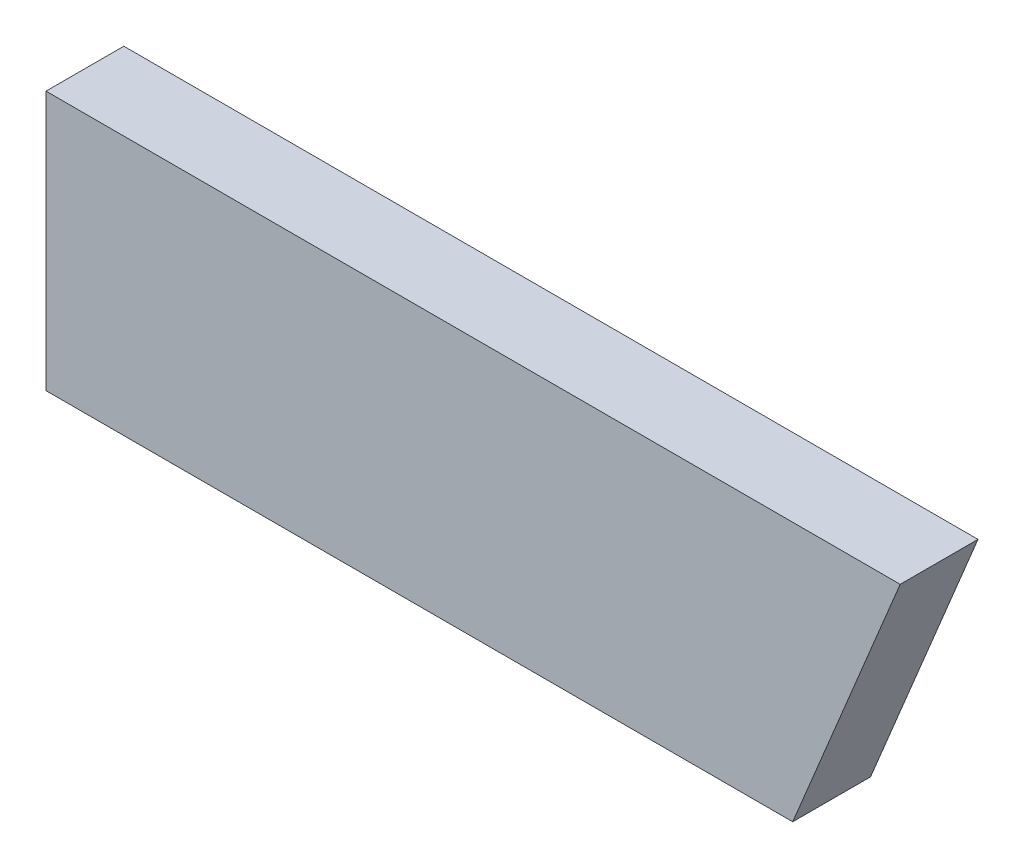
SolidWorks part; units mm, degrees
material "Pine"
ref_plane "Front Plane" through (0, 0, 0) normal (0, 0, 1) x (1, 0, 0)
ref_plane "Top Plane" through (0, 0, 0) normal (0, 1, 0) x (1, 0, 0)
ref_plane "Right Plane" through (0, 0, 0) normal (1, 0, 0) x (0, 0, -1)
sketch "Sketch2" plane through (0, 0, 0) normal (0, 0, 1) x (1, 0, 0)
  line L0 (-528.0858, 1843.9468) -> (-737.1845, 1843.9468)
  line L1 (-737.1845, 1780.4468) -> (-737.1845, 1843.9468)
  line L2 (-528.0858, 1843.9468) -> (-554.3883, 1780.4468)
  line L3 (-737.1845, 1780.4468) -> (-554.3883, 1780.4468)
extrude "Boss-Extrude1" add sketch "Sketch2" along normal blind 19.05
